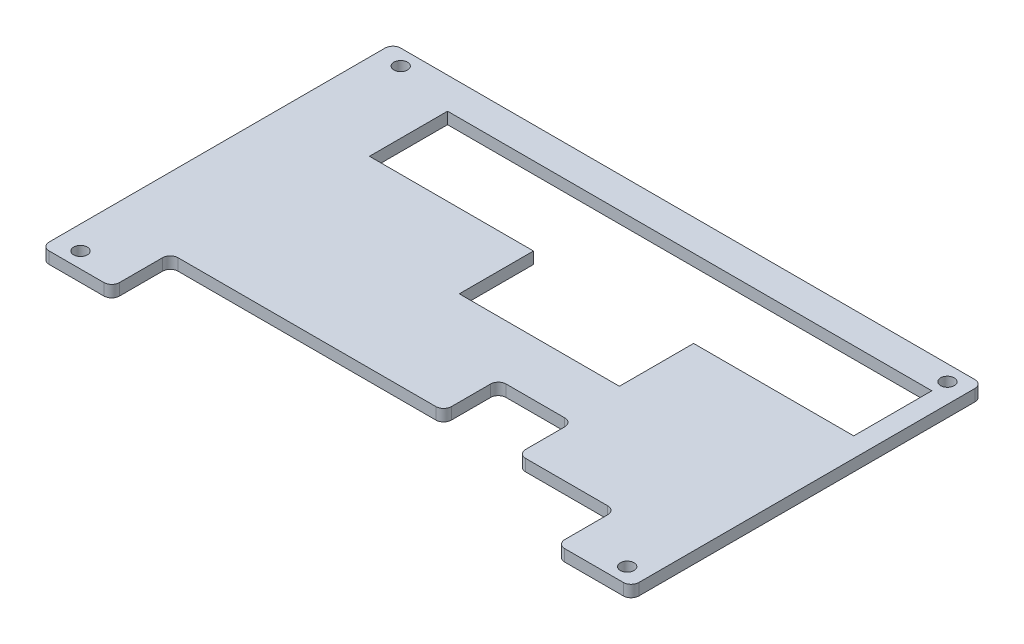
SolidWorks part; units mm, degrees
ref_plane "Front Plane" through (0, 0, 0) normal (0, 0, 1) x (1, 0, 0)
ref_plane "Top Plane" through (0, 0, 0) normal (0, 1, 0) x (1, 0, 0)
ref_plane "Right Plane" through (0, 0, 0) normal (1, 0, 0) x (0, 0, -1)
sketch "Sketch1" plane through (0, 0, 0) normal (0, 1, 0) x (1, 0, 0)
  line L1 (0, 0) -> (151, 0)
  line L2 (0, 0) -> (0, 90)
  line L3 (0, 90) -> (151, 90)
  line L4 (151, 0) -> (151, 90)
  dimension "D1" = 151
  dimension "D2" = 90
extrude "Boss-Extrude1" add sketch "Sketch1" along normal blind 3
sketch "Sketch2" plane through (0, 3, 0) normal (0, 1, 0) x (1, 0, 0)
  line L0 (151, 0) -> (151, 90) construction
  line L1 (151, 90) -> (0, 90) construction
  line L2 (0, 0) -> (151, 0) construction
  line L3 (0, 90) -> (0, 0) construction
  circle A0 centre (146, 86) radius 1.75
  circle A1 centre (146, 4) radius 1.75
  circle A2 centre (6, 86) radius 1.75
  circle A3 centre (6, 4) radius 1.75
  dimension "D1" = 3.5
  dimension "D2" = 5
  dimension "D3" = 4
  dimension "D4" = 3.5
  dimension "D5" = 5
  dimension "D6" = 4
  dimension "D7" = 4
  dimension "D8" = 6
  dimension "D9" = 3.5
  dimension "D10" = 3.5
  dimension "D11" = 6
  dimension "D12" = 4
extrude "Cut-Extrude1" cut sketch "Sketch2" against normal through all
fillet "Fillet1" radius 2 4 edges at (151, 1.5, -90) (151, 1.5, 0) (0, 1.5, 0) (0, 1.5, -90)
sketch "Sketch3" plane through (0, 3, 0) normal (0, 1, 0) x (1, 0, 0)
  line L0 (105, 62) -> (146, 62)
  line L1 (22, 82) -> (146, 82)
  line L2 (22, 82) -> (22, 62)
  line L3 (22, 62) -> (64, 62)
  line L4 (146, 82) -> (146, 62)
  line L6 (64, 62) -> (64, 43)
  line L7 (64, 43) -> (105, 43)
  line L8 (105, 62) -> (105, 43)
  line L9 (0, 88) -> (0, 2) construction
  line L10 (151, 2) -> (151, 88) construction
  line L11 (149, 90) -> (2, 90) construction
  line L12 (2, 0) -> (149, 0) construction
  line L13 (18, 0) -> (132, 0)
  line L14 (18, 0) -> (18, 15)
  line L15 (18, 15) -> (88, 15)
  line L16 (132, 0) -> (132, 15)
  line L17 (107, 15) -> (132, 15)
  line L19 (88, 15) -> (88, 29)
  line L20 (88, 29) -> (107, 29)
  line L21 (107, 15) -> (107, 29)
  dimension "D1" = 22
  dimension "D2" = 5
  dimension "D3" = 8
  dimension "D4" = 20
  dimension "D5" = 42
  dimension "D6" = 41
  dimension "D7" = 47
  dimension "D8" = 18
  dimension "D9" = 70
  dimension "D10" = 14
  dimension "D11" = 15
  dimension "D12" = 19
  dimension "D13" = 25
extrude "Cut-Extrude2" cut sketch "Sketch3" against normal through all
fillet "Fillet2" radius 2 8 edges at (132, 1.5, 0) (132, 1.5, -15) (107, 1.5, -15) (107, 1.5, -29) (88, 1.5, -29) (88, 1.5, -15) (18, 1.5, -15) (18, 1.5, 0)
